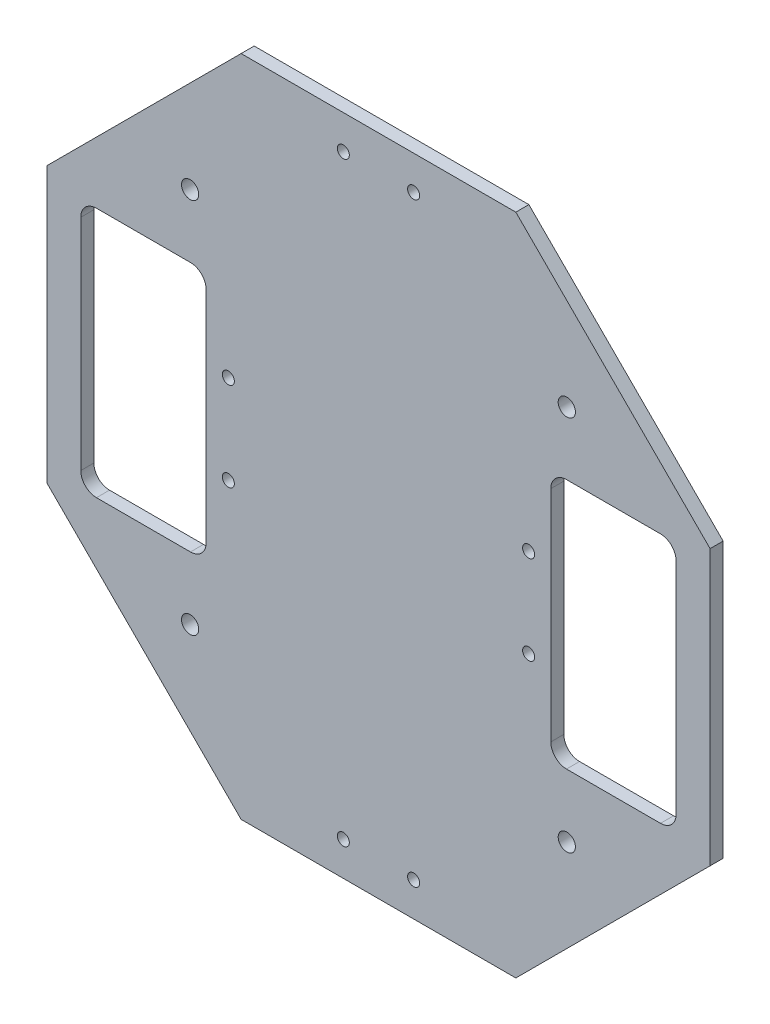
SolidWorks part; units mm, degrees
ref_plane "Plano frontal" through (0, 0, 0) normal (0, 0, 1) x (1, 0, 0)
ref_plane "Plano superior" through (0, 0, 0) normal (0, 1, 0) x (1, 0, 0)
ref_plane "Plano direito" through (0, 0, 0) normal (1, 0, 0) x (0, 0, -1)
sketch "Esboço1" plane through (0, 0, 0) normal (0, 0, 1) x (1, 0, 0)
  line L1 (63.5, -26.3026) -> (63.5, 26.3026)
  line L2 (63.5, 26.3026) -> (26.3026, 63.5)
  line L3 (26.3026, 63.5) -> (-26.3026, 63.5)
  line L4 (-26.3026, 63.5) -> (-63.5, 26.3026)
  line L5 (-63.5, 26.3026) -> (-63.5, -26.3026)
  line L6 (-63.5, -26.3026) -> (-26.3026, -63.5)
  line L7 (-26.3026, -63.5) -> (26.3026, -63.5)
  line L8 (26.3026, -63.5) -> (63.5, -26.3026)
  circle A0 centre (0, 0) radius 63.5 construction
  dimension "D1" = 127
extrude "Ressalto-extrusão1" add sketch "Esboço1" along normal blind 2.5
sketch "Esboço3"
sketch "Esboço2" plane through (0, 0, 0) normal (0, 0, -1) x (-1, 0, 0)
  line L0 (-45, 0) -> (45, 0) construction
  line L1 (-28.75, 0) -> (28.75, 0) construction
  line L2 (28.75, 0) -> (28.75, 8.5) construction
  line L3 (0, 0) -> (0, 75.734) construction
  line L4 (54, 24) -> (36, 24)
  line L5 (57, 21) -> (57, -21)
  line L6 (54, -24) -> (36, -24)
  line L7 (33, 21) -> (33, -21)
  line L8 (57, 24) -> (33, -24) construction
  line L9 (57, -24) -> (33, 24) construction
  line L10 (-57, -24) -> (-33, 24) construction
  line L11 (-57, 24) -> (-33, -24) construction
  line L12 (-28.75, 0) -> (-28.75, 8.5) construction
  line L13 (-33, 21) -> (-33, -21)
  line L14 (-54, -24) -> (-36, -24)
  line L15 (-57, 21) -> (-57, -21)
  line L16 (-54, 24) -> (-36, 24)
  line L17 (0, 0) -> (0, -57) construction
  line L18 (0, -57) -> (-6.731, -57) construction
  circle A0 centre (28.75, 8.5) radius 1.15
  circle A1 centre (28.75, -8.5) radius 1.15
  arc A2 (36, 24) -> (33, 21) centre (36, 21) ccw
  arc A3 (36, -24) -> (33, -21) centre (36, -21) cw
  arc A4 (57, -21) -> (54, -24) centre (54, -21) cw
  arc A5 (54, 24) -> (57, 21) centre (54, 21) cw
  arc A6 (-54, 24) -> (-57, 21) centre (-54, 21) ccw
  arc A7 (-57, -21) -> (-54, -24) centre (-54, -21) ccw
  arc A8 (-36, -24) -> (-33, -21) centre (-36, -21) ccw
  arc A9 (-36, 24) -> (-33, 21) centre (-36, 21) cw
  circle A10 centre (-28.75, -8.5) radius 1.15
  circle A11 centre (-28.75, 8.5) radius 1.15
  circle A12 centre (-6.731, -57) radius 1.15
  circle A13 centre (6.731, -57) radius 1.15
  circle A14 centre (6.731, 57) radius 1.15
  circle A15 centre (-6.731, 57) radius 1.15
  dimension "D6" = 3
  dimension "D8" = 6.731
  dimension "D1" = 45
  dimension "D2" = 48
  dimension "D3" = 24
  dimension "D4" = 28.75
  dimension "D5" = 8.5
  dimension "D7" = 57
extrude "Corte-extrusão1" cut sketch "Esboço2" against normal through all
sketch "Esboço4" plane through (0, 0, 0) normal (0, 0, -1) x (-1, 0, 0)
  line L0 (0, 0) -> (36.0624, 36.0624) construction
  circle A0 centre (0, 0) radius 51 construction
  circle A1 centre (36.0624, -36.0624) radius 1.65
  circle A2 centre (36.0624, 36.0624) radius 1.65
  circle A3 centre (-36.0624, -36.0624) radius 1.65
  circle A4 centre (-36.0624, 36.0624) radius 1.65
  point P7 (0, 0)
  point P14 (0, 0)
  point P15 (0, 0)
  dimension "D1" = 4
extrude "Corte-extrusão2" cut sketch "Esboço4" against normal blind 40.5
